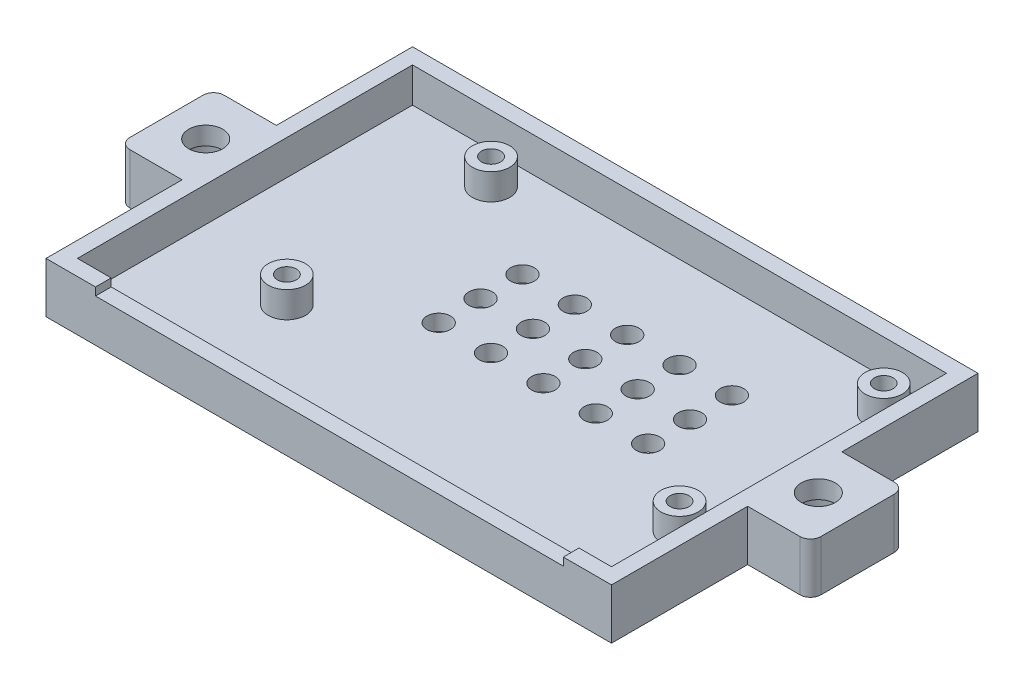
SolidWorks part; units mm, degrees
ref_plane "Front Plane" through (0, 0, 0) normal (0, 0, 1) x (1, 0, 0)
ref_plane "Top Plane" through (0, 0, 0) normal (0, 1, 0) x (1, 0, 0)
ref_plane "Right Plane" through (0, 0, 0) normal (1, 0, 0) x (0, 0, -1)
sketch "Sketch2" plane through (0, 0, 0) normal (0, 1, 0) x (1, 0, 0)
  line L0 (-37.2311, 32.3785) -> (37.7689, -6.6215) construction
  line L1 (-57.2311, 37.3785) -> (42.7689, 37.3785) construction
  line L2 (-57.2311, 37.3785) -> (-57.2311, -24.6215) construction
  line L3 (-57.2311, -24.6215) -> (42.7689, -24.6215) construction
  line L4 (42.7689, 37.3785) -> (42.7689, -24.6215) construction
  line L5 (-37.2311, -6.6215) -> (37.7689, 32.3785) construction
  line L7 (-58.2311, 38.3785) -> (43.7689, 38.3785) construction
  line L8 (-58.2311, 38.3785) -> (-58.2311, -25.6215) construction
  line L9 (-58.2311, -25.6215) -> (43.7689, -25.6215) construction
  line L10 (43.7689, 38.3785) -> (43.7689, -25.6215) construction
  line L11 (-61.2311, 41.3785) -> (46.7689, 41.3785)
  line L12 (-61.2311, 41.3785) -> (-61.2311, -28.6215)
  line L13 (-61.2311, -28.6215) -> (46.7689, -28.6215)
  line L14 (46.7689, 41.3785) -> (46.7689, -28.6215)
  circle A0 centre (20.2689, 4.8785) radius 2.25
  circle A1 centre (10.2689, 4.8785) radius 2.25
  circle A2 centre (0.2689, 4.8785) radius 2.25
  circle A3 centre (10.2689, 12.8785) radius 2.25
  circle A4 centre (0.2689, 12.8785) radius 2.25
  circle A5 centre (10.2689, 20.8785) radius 2.25
  circle A6 centre (0.2689, 20.8785) radius 2.25
  circle A7 centre (20.2689, 12.8785) radius 2.25
  circle A8 centre (20.2689, 20.8785) radius 2.25
  circle A9 centre (-9.7311, 4.8785) radius 2.25
  circle A10 centre (-9.7311, 12.8785) radius 2.25
  circle A11 centre (-9.7311, 20.8785) radius 2.25
  circle A12 centre (-19.7311, 4.8785) radius 2.25
  circle A13 centre (-19.7311, 12.8785) radius 2.25
  circle A14 centre (-19.7311, 20.8785) radius 2.25
  point P4 (-37.2311, 32.3785)
  point P5 (37.7689, 32.3785)
  point P6 (37.7689, -6.6215)
  point P7 (-37.2311, -6.6215)
  point P9 (20.2689, 4.8785)
  point P38 (-37.2311, 32.3785)
  point P41 (0.2689, 12.8785)
  dimension "D11" = 4.5
  dimension "D12" = 5
  dimension "D1" = 62
  dimension "D2" = 100
  dimension "D3" = 5
  dimension "D4" = 20
  dimension "D5" = 5
  dimension "D6" = 5
  dimension "D7" = 18
  dimension "D8" = 20
  dimension "D9" = 18
  dimension "D10" = 5
  dimension "D13" = 3
  dimension "D14" = 1
  dimension "D15" = 3
  dimension "D16" = 1
  dimension "D17" = 3
  dimension "D18" = 1
  dimension "D19" = 3
  dimension "D20" = 1
  dimension "D21" = 3
extrude "Boss-Extrude1" add sketch "Sketch2" against normal blind 3
sketch "Sketch5" plane through (0, 0, 0) normal (0, 1, 0) x (1, 0, 0)
  circle A0 centre (-37.2311, 32.3785) radius 3.5635
  circle A1 centre (37.7689, 32.3785) radius 3.5635
  circle A2 centre (37.7689, -6.6215) radius 3.5635
  circle A3 centre (-37.2311, -6.6215) radius 3.5635
  circle A4 centre (-37.2311, 32.3785) radius 1.8135
  circle A5 centre (37.7689, 32.3785) radius 1.8135
  circle A6 centre (37.7689, -6.6215) radius 1.8135
  circle A7 centre (-37.2311, -6.6215) radius 1.8135
  dimension "D1" = 7.127
  dimension "D4" = 3.627
  dimension "D2" = 2
  dimension "D3" = 2
extrude "Boss-Extrude2" add sketch "Sketch5" along normal blind 5
sketch "Sketch6" plane through (0, 0, 0) normal (0, 1, 0) x (1, 0, 0)
  circle A0 centre (-37.2311, 32.3785) radius 1.8135
  circle A1 centre (37.7689, 32.3785) radius 1.8135
  circle A2 centre (37.7689, -6.6215) radius 1.8135
  circle A3 centre (-37.2311, -6.6215) radius 1.8135
extrude "Boss-Extrude3" add sketch "Sketch6" along normal blind 2
sketch "Sketch7" plane through (0, 0, 0) normal (0, 1, 0) x (1, 0, 0)
  line L2 (-58.2311, 38.3785) -> (43.7689, 38.3785)
  line L3 (-58.2311, 38.3785) -> (-58.2311, -25.6215)
  line L4 (-58.2311, -25.6215) -> (43.7689, -25.6215)
  line L5 (43.7689, 38.3785) -> (43.7689, -25.6215)
  line L6 (-61.2311, 41.3785) -> (46.7689, 41.3785)
  line L7 (-61.2311, 41.3785) -> (-61.2311, -28.6215)
  line L8 (-61.2311, -28.6215) -> (46.7689, -28.6215)
  line L9 (46.7689, 41.3785) -> (46.7689, -28.6215)
extrude "Boss-Extrude4" add sketch "Sketch7" along normal blind 6.65
sketch "Sketch9" plane through (0, 6.65, 0) normal (0, 1, 0) x (1, 0, 0)
  line L0 (-58.2311, -25.6215) -> (43.7689, -25.6215) construction
  line L1 (-51.7811, -25.6215) -> (37.5689, -25.6215)
  line L2 (-51.7811, -25.6215) -> (-51.7811, -28.6215)
  line L3 (-51.7811, -28.6215) -> (37.5689, -28.6215)
  line L4 (37.5689, -25.6215) -> (37.5689, -28.6215)
  line L5 (-61.2311, -28.6215) -> (46.7689, -28.6215) construction
  line L6 (-58.2311, 38.3785) -> (-58.2311, -25.6215) construction
  line L8 (43.7689, -25.6215) -> (43.7689, 38.3785) construction
  dimension "D1" = 6.45
  dimension "D2" = 6.2
extrude "Cut-Extrude1" cut sketch "Sketch9" against normal blind 1.5
sketch "Sketch11" plane through (0, -3, 0) normal (0, -1, 0) x (1, 0, 0)
  line L0 (-61.2311, -41.3785) -> (-61.2311, 28.6215) construction
  line L1 (-61.2311, -6.3785) -> (-48.4788, -6.3785) construction
  line L2 (46.7689, -41.3785) -> (-61.2311, -41.3785) construction
  line L3 (-61.2311, 2.6215) -> (-73.2311, 2.6215)
  line L4 (-61.2311, 2.6215) -> (-61.2311, -15.3785)
  line L5 (-61.2311, -15.3785) -> (-73.2311, -15.3785)
  line L6 (-73.2311, 2.6215) -> (-73.2311, -15.3785)
  line L7 (-7.2311, -41.3785) -> (-7.2311, -29.4534) construction
  line L8 (46.7689, -15.3785) -> (58.7689, -15.3785)
  line L9 (58.7689, 2.6215) -> (58.7689, -15.3785)
  line L10 (46.7689, 2.6215) -> (58.7689, 2.6215)
  line L11 (46.7689, 2.6215) -> (46.7689, -15.3785)
  line L12 (46.7689, 28.6215) -> (46.7689, -41.3785) construction
  circle A0 centre (-65.7311, -6.3785) radius 3.25
  circle A1 centre (51.2689, -6.3785) radius 3.25
  point P8 (-73.2311, -6.3785)
  dimension "D3" = 6.5
  dimension "D1" = 18
  dimension "D2" = 12
  dimension "D4" = 7.5
extrude "Boss-Extrude5" add sketch "Sketch11" against normal up to surface (9.65 mm away) up to face at (-7.1894, 6.65, 4.7882)
fillet "Fillet1" radius 2 4 edges at (58.7689, 1.825, 2.6215) (58.7689, 1.825, -15.3785) (-73.2311, 1.825, -15.3785) (-73.2311, 1.825, 2.6215)
sketch "Sketch12" plane through (0, -3, 0) normal (0, -1, 0) x (1, 0, 0)
  circle A0 centre (-65.7311, -6.3785) radius 5.5
  circle A1 centre (51.2689, -6.3785) radius 5.5
  dimension "D1" = 11
  dimension "D2" = 11
extrude "Cut-Extrude2" cut sketch "Sketch12" against normal blind 6.2
